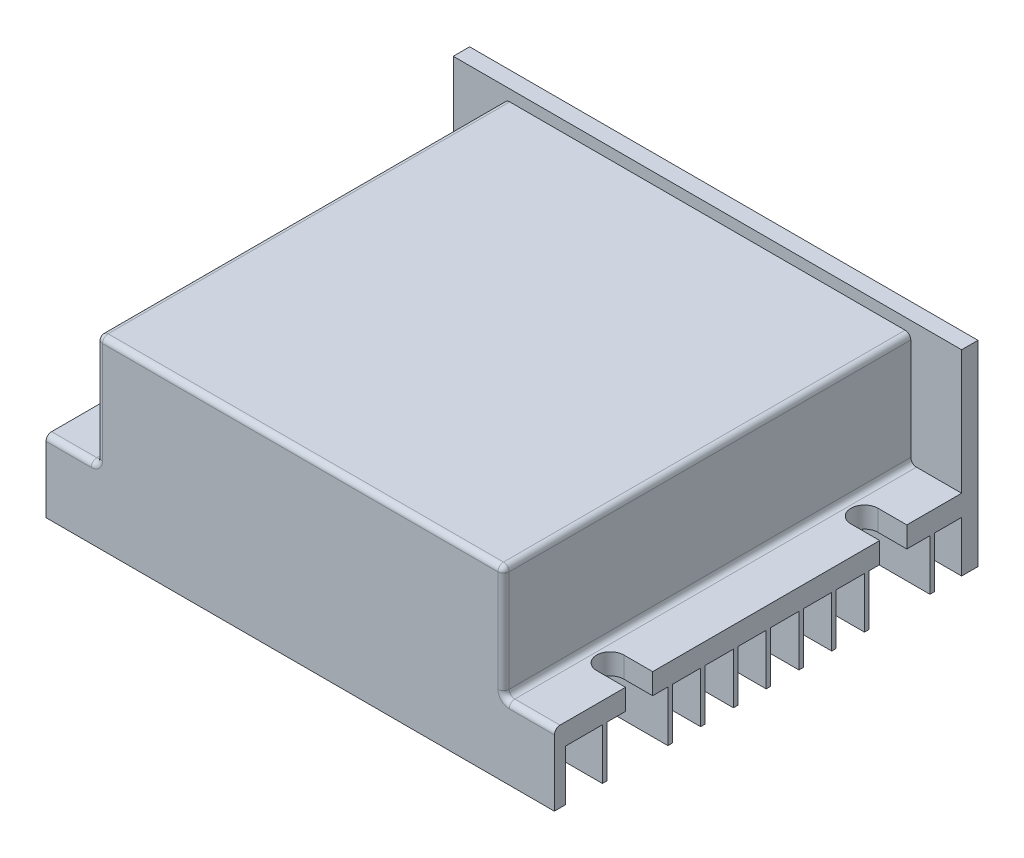
SolidWorks part; units mm, degrees
ref_plane "Plan de face" through (0, 0, 0) normal (0, 0, 1) x (1, 0, 0)
ref_plane "Plan de dessus" through (0, 0, 0) normal (0, 1, 0) x (1, 0, 0)
ref_plane "Plan de droite" through (0, 0, 0) normal (1, 0, 0) x (0, 0, -1)
sketch "Esquisse1" plane through (0, 0, 0) normal (0, 1, 0) x (1, 0, 0)
  line L1 (0, 0) -> (90, 0)
  line L2 (0, 0) -> (0, 75)
  line L3 (0, 75) -> (90, 75)
  line L4 (90, 0) -> (90, 75)
  dimension "D1" = 75
  dimension "D2" = 90
extrude "Boss.-Extru.1" add sketch "Esquisse1" along normal blind 3.7
sketch "Esquisse2" plane through (0, 0, 0) normal (0, -1, 0) x (1, 0, 0)
  line L0 (90, 0) -> (90, -75) construction
  line L1 (0, -75) -> (90, -75)
  line L2 (0, -75) -> (0, -72.1)
  line L3 (0, -72.1) -> (90, -72.1)
  line L4 (90, -75) -> (90, -72.1)
  line L5 (0, -75) -> (0, 0) construction
  line L6 (0, 0) -> (90, 0)
  line L7 (0, 0) -> (0, -2)
  line L8 (0, -2) -> (90, -2)
  line L9 (90, 0) -> (90, -2)
  line L10 (0, -67.3) -> (90, -67.3)
  line L11 (0, -67.3) -> (0, -66.5)
  line L12 (0, -66.5) -> (90, -66.5)
  line L13 (90, -67.3) -> (90, -66.5)
  line L14 (0, -60.7) -> (90, -60.7)
  line L15 (0, -61.5) -> (90, -61.5)
  line L16 (0, -61.5) -> (0, -60.7)
  line L17 (90, -61.5) -> (90, -60.7)
  line L18 (0, -54.9) -> (90, -54.9)
  line L19 (0, -55.7) -> (90, -55.7)
  line L20 (0, -55.7) -> (0, -54.9)
  line L21 (90, -55.7) -> (90, -54.9)
  line L22 (0, -49.1) -> (90, -49.1)
  line L23 (0, -49.9) -> (90, -49.9)
  line L24 (0, -49.9) -> (0, -49.1)
  line L25 (90, -49.9) -> (90, -49.1)
  line L26 (0, -43.3) -> (90, -43.3)
  line L27 (0, -44.1) -> (90, -44.1)
  line L28 (0, -44.1) -> (0, -43.3)
  line L29 (90, -44.1) -> (90, -43.3)
  line L30 (0, -37.5) -> (90, -37.5)
  line L31 (0, -38.3) -> (90, -38.3)
  line L32 (0, -38.3) -> (0, -37.5)
  line L33 (90, -38.3) -> (90, -37.5)
  line L34 (0, -31.7) -> (90, -31.7)
  line L35 (0, -32.5) -> (90, -32.5)
  line L36 (0, -32.5) -> (0, -31.7)
  line L37 (90, -32.5) -> (90, -31.7)
  line L38 (0, -25.9) -> (90, -25.9)
  line L39 (0, -26.7) -> (90, -26.7)
  line L40 (0, -26.7) -> (0, -25.9)
  line L41 (90, -26.7) -> (90, -25.9)
  line L42 (0, -20.1) -> (90, -20.1)
  line L43 (0, -20.9) -> (90, -20.9)
  line L44 (0, -20.9) -> (0, -20.1)
  line L45 (90, -20.9) -> (90, -20.1)
  line L46 (0, -14.3) -> (90, -14.3)
  line L47 (0, -15.1) -> (90, -15.1)
  line L48 (0, -15.1) -> (0, -14.3)
  line L49 (90, -15.1) -> (90, -14.3)
  line L50 (0, -8.5) -> (90, -8.5)
  line L51 (0, -9.3) -> (90, -9.3)
  line L52 (0, -9.3) -> (0, -8.5)
  line L53 (90, -9.3) -> (90, -8.5)
  dimension "D1" = 2.9
  dimension "D2" = 2
  dimension "D3" = 0.8
  dimension "D4" = 4.8
  dimension "D5" = 11
extrude "Boss.-Extru.2" add sketch "Esquisse2" along normal blind 9
sketch "Esquisse3" plane through (0, 3.7, 0) normal (0, 1, 0) x (1, 0, 0)
  line L0 (45, -21.4737) -> (45, 104.5277) construction
  line L1 (90, 0) -> (90, 75) construction
  line L2 (0, 75) -> (0, 0) construction
  line L3 (106.4061, 37.5) -> (-23.5255, 37.5) construction
  line L4 (0, 0) -> (90, 0) construction
  line L5 (90, 75) -> (0, 75) construction
  line L6 (92.9863, 15) -> (82.7962, 15) construction
  line L7 (90, 12.6) -> (84.9, 12.6)
  line L8 (84.9, 17.4) -> (90, 17.4)
  line L9 (90, 17.4) -> (90, 12.6)
  line L10 (92.9863, 60) -> (82.7962, 60) construction
  line L11 (84.9, 57.6) -> (90, 57.6)
  line L12 (90, 62.4) -> (84.9, 62.4)
  line L13 (90, 57.6) -> (90, 62.4)
  line L14 (-2.9863, 60) -> (7.2038, 60) construction
  line L15 (0, 57.6) -> (0, 62.4)
  line L16 (0, 62.4) -> (5.1, 62.4)
  line L17 (5.1, 57.6) -> (0, 57.6)
  line L18 (-2.9863, 15) -> (7.2038, 15) construction
  line L19 (0, 17.4) -> (0, 12.6)
  line L20 (5.1, 17.4) -> (0, 17.4)
  line L21 (0, 12.6) -> (5.1, 12.6)
  arc A0 (84.9, 12.6) -> (84.9, 17.4) centre (84.9, 15) cw
  arc A1 (84.9, 62.4) -> (84.9, 57.6) centre (84.9, 60) ccw
  arc A2 (5.1, 62.4) -> (5.1, 57.6) centre (5.1, 60) cw
  arc A3 (5.1, 12.6) -> (5.1, 17.4) centre (5.1, 15) ccw
  dimension "D1" = 4.8
  dimension "D2" = 5.1
  dimension "D3" = 45
extrude "Enlèv. mat.-Extru.1" cut sketch "Esquisse3" against normal through all
sketch "Esquisse4" plane through (0, 3.7, 0) normal (0, 1, 0) x (1, 0, 0)
  line L0 (0, 75) -> (0, 62.4) construction
  line L1 (90, 75) -> (0, 75)
  line L2 (90, 75) -> (90, 72.1)
  line L3 (90, 72.1) -> (0, 72.1)
  line L4 (0, 75) -> (0, 72.1)
  line L5 (90, 72.1) -> (0, 72.1) construction
extrude "Boss.-Extru.3" add sketch "Esquisse4" along normal blind 22
sketch "Esquisse5" plane through (0, 3.7, 0) normal (0, 1, 0) x (1, 0, 0)
  line L0 (45, 112.219) -> (45, -33.9916) construction
  line L1 (0, 57.6) -> (0, 17.4) construction
  line L2 (90, 17.4) -> (90, 57.6) construction
  line L3 (0, 72.1) -> (90, 72.1) construction
  line L4 (9, 72.1) -> (81, 72.1)
  line L5 (9, 72.1) -> (9, 0)
  line L6 (9, 0) -> (81, 0)
  line L7 (81, 72.1) -> (81, 0)
  line L8 (0, 0) -> (90, 0) construction
  dimension "D1" = 72
extrude "Boss.-Extru.4" add sketch "Esquisse5" along normal blind 20
fillet "Congé1" radius 1 9 edges at (4.5, 3.7, 0) (85.5, 3.7, 0) (9, 3.7, -36.05) (81, 13.7, 0) (81, 3.7, -36.05) (81, 23.7, -36.05) (9, 13.7, 0) (45, 23.7, 0) (9, 23.7, -36.05)
